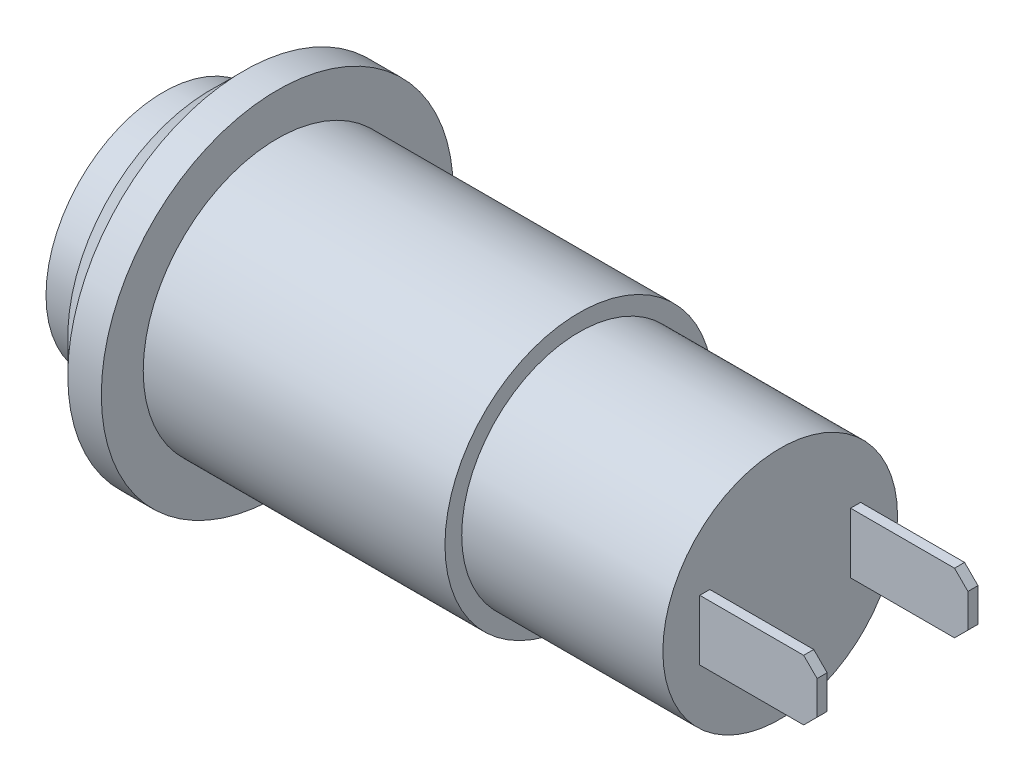
SolidWorks part; units mm, degrees
ref_plane "前视基准面" through (0, 0, 0) normal (0, 0, 1) x (1, 0, 0)
ref_plane "上视基准面" through (0, 0, 0) normal (0, 1, 0) x (1, 0, 0)
ref_plane "右视基准面" through (0, 0, 0) normal (1, 0, 0) x (0, 0, -1)
sketch "草图2" plane through (0, 0, 0) normal (0, 0, 1) x (1, 0, 0)
  line L5 (0, 0) -> (18.4, 0) construction
  line L16 (18.4, 0) -> (18.4, 3.5)
  line L17 (18.4, 3.5) -> (12.4, 3.5)
  line L18 (12.4, 3.5) -> (12.4, 4)
  line L19 (12.4, 4) -> (3.4, 4)
  line L20 (3.4, 4) -> (3.4, 5.25)
  line L21 (3.4, 5.25) -> (1.4, 5.25)
  line L22 (1.4, 5.25) -> (1.4, 3.5)
  line L23 (1.4, 3.5) -> (0, 3.5)
  line L24 (0, 3.5) -> (0, 0)
  line L25 (0, 0) -> (18.4, 0)
  dimension "D1" = 8
  dimension "D2" = 7
  dimension "D3" = 7
  dimension "D4" = 10.5
  dimension "D5" = 2
  dimension "D6" = 1.4
  dimension "D7" = 9
  dimension "D8" = 18.4
revolve "旋转3" add sketch "草图2" angle 360 about L5
cosmetic thread "装饰螺纹线1" parameters "D2"=6.647
chamfer "倒角1" distance 1 angle 45 1 edges at (1.4, 0, 5.25)
sketch "草图4" plane through (18.4, 0, 0) normal (1, 0, 0) x (0, 0, -1)
  line L0 (-2.25, 0) -> (2.25, 0) construction
  line L1 (0, -3.1316) -> (0, 3.1316) construction
  line L2 (-2.1, -0.9) -> (-2.4, -0.9)
  line L3 (-2.1, -0.9) -> (-2.1, 0.9)
  line L4 (-2.1, 0.9) -> (-2.4, 0.9)
  line L5 (-2.4, -0.9) -> (-2.4, 0.9)
  line L6 (-2.1, -0.9) -> (-2.4, 0.9) construction
  line L7 (-2.1, 0.9) -> (-2.4, -0.9) construction
  line L8 (2.1, -0.9) -> (2.4, -0.9)
  line L9 (2.1, -0.9) -> (2.1, 0.9)
  line L10 (2.1, 0.9) -> (2.4, 0.9)
  line L11 (2.4, -0.9) -> (2.4, 0.9)
  line L12 (2.1, -0.9) -> (2.4, 0.9) construction
  line L13 (2.1, 0.9) -> (2.4, -0.9) construction
  point P3 (0, 0)
  point P4 (0, 0)
  point P15 (0, 0)
  dimension "D1" = 1.8
  dimension "D2" = 0.3
  dimension "D3" = 4.8
extrude "凸台-拉伸1" add sketch "草图4" along normal blind 3.5
chamfer "倒角2" distance 0.4 angle 45 4 edges at (21.9, -0.9, 2.25) (21.9, -0.9, -2.25) (21.9, 0.9, 2.25) (21.9, 0.9, -2.25)
